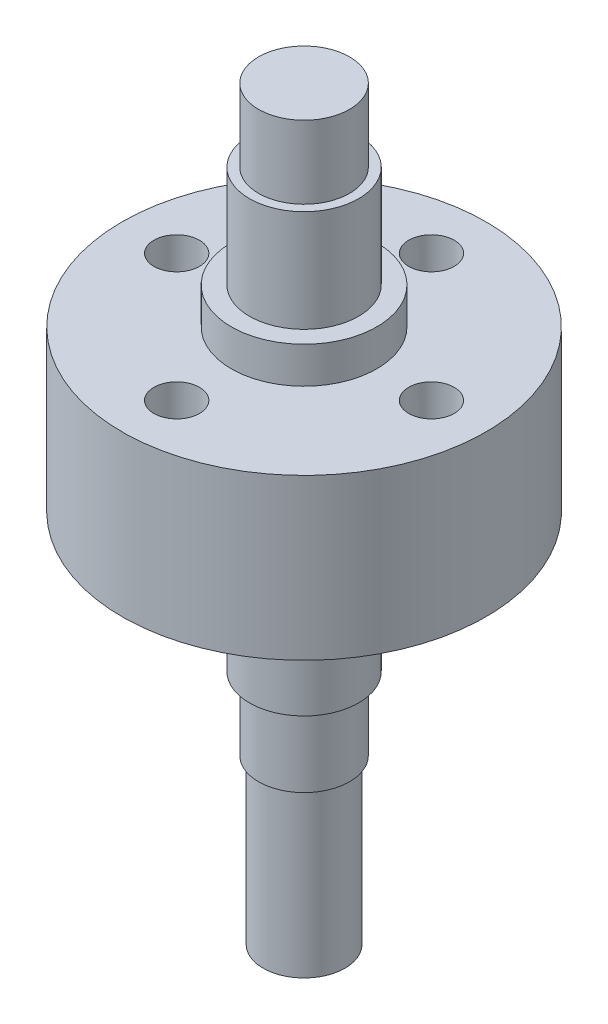
SolidWorks part; units mm, degrees
material "6061 合金"
ref_plane "前视基准面" through (0, 0, 0) normal (0, 0, 1) x (1, 0, 0)
ref_plane "上视基准面" through (0, 0, 0) normal (0, 1, 0) x (1, 0, 0)
ref_plane "右视基准面" through (0, 0, 0) normal (1, 0, 0) x (0, 0, -1)
sketch "Model" plane through (0, 0, 0) normal (0, 0, 1) x (1, 0, 0)
  line L0 (0, 32) -> (0, 0)
  line L1 (10, 11.6) -> (10, 20.4)
  line L3 (4, 20.4) -> (4, 22.4)
  line L5 (4, 9.6) -> (4, 11.6)
  line L7 (3, 4) -> (3, 9.6)
  line L9 (3, 22.4) -> (3, 28)
  line L11 (2.5, 0) -> (2.5, 4)
  line L13 (2.5, 28) -> (2.5, 32)
  line L16 (3, 22.4) -> (4, 22.4)
  line L20 (0, 0) -> (2.5, 0)
  line L21 (0, 32) -> (2.5, 32)
  line L22 (0, 32) -> (0, 0) construction
  line L23 (2.5, 28) -> (3, 28)
  line L24 (4, 20.4) -> (10, 20.4)
  line L25 (4, 11.6) -> (10, 11.6)
  line L26 (3, 9.6) -> (4, 9.6)
  line L27 (2.5, 4) -> (3, 4)
  dimension "D1" = 4
  dimension "D2" = 5.6
  dimension "D3" = 2
  dimension "D4" = 8.8
  dimension "D5" = 2
  dimension "D6" = 5.6
  dimension "D7" = 4
  dimension "D8" = 2.5
  dimension "D9" = 3
  dimension "D10" = 4
  dimension "D11" = 10
  dimension "D12" = 4
  dimension "D13" = 3
  dimension "D14" = 2.5
revolve "旋转1" add sketch "Model" angle 360 about L22
sketch "草图2" plane through (0, 11.6, 0) normal (0, -1, 0) x (1, 0, 0)
  circle A0 centre (0, 0) radius 7 construction
  circle A1 centre (0, 7) radius 1.5
  dimension "D1" = 14
  dimension "D2" = 3
hole_wizard "M3 螺纹孔1" positions "3D草图1" profile "草图4" tap size "M3" standard "GB" end condition through all
sketch3d "3D草图1"
  point P0 (0, 11.6, 7)
sketch "草图4" plane through (0, 11.6, 7) normal (1, 0, 0) x (0, 0, -1)
  line L0 (0, 0) -> (0, 20.4)
  line L1 (0, 20.4) -> (1.25, 20.4)
  line L2 (1.25, 20.4) -> (1.25, 0)
  line L5 (1.25, 0) -> (0, 0)
  line L11 (0, -6.35) -> (0, 107.95) construction
  dimension "通孔螺纹孔钻头直径" = 2.5
  dimension "通孔螺纹孔钻头深度" = 20.4
cosmetic thread "孔螺蚊线1" parameters "D2"=3
pattern_circular "阵列(圆周)1" count 4 over 360 about axis through (0, 0, 0) along (0, 1, 0) of "M3 螺纹孔1"
sketch "草图5" plane through (0, 0, 0) normal (0, -1, 0) x (1, 0, 0)
  circle A0 centre (0, 0) radius 2.25
  dimension "D1" = 4.5
extrude "凸台-拉伸1" add sketch "草图5" along normal blind 9
sketch "草图7" plane through (0, -9, 0) normal (0, -1, 0) x (1, 0, 0)
  circle A0 centre (0, 0) radius 1.5
  point P4 (0, 0)
  dimension "D1" = 3
hole_wizard "M3 螺纹孔2" positions "草图8" profile "草图9" tap size "M3" standard "GB"
sketch "草图8" plane through (0, -9, 0) normal (0, -1, 0) x (-1, 0, 0)
  point P0 (0, 0)
sketch "草图9" plane through (0, -9, 0) normal (1, 0, 0) x (0, 0, -1)
  line L0 (0, 0) -> (0, 12.7511)
  line L1 (0, 12.7511) -> (1.25, 12)
  line L2 (1.25, 12) -> (1.25, 0)
  line L5 (1.25, 0) -> (0, 0)
  line L10 (0, 12.7511) -> (-1.25, 12) construction
  line L11 (0, -6.35) -> (0, 107.95) construction
  dimension "螺纹孔钻头直径" = 2.5
  dimension "螺纹孔钻头深度" = 12
  dimension "导头角度" = 118
cosmetic thread "孔螺纹线1" parameters "D1"=8, "D2"=3
